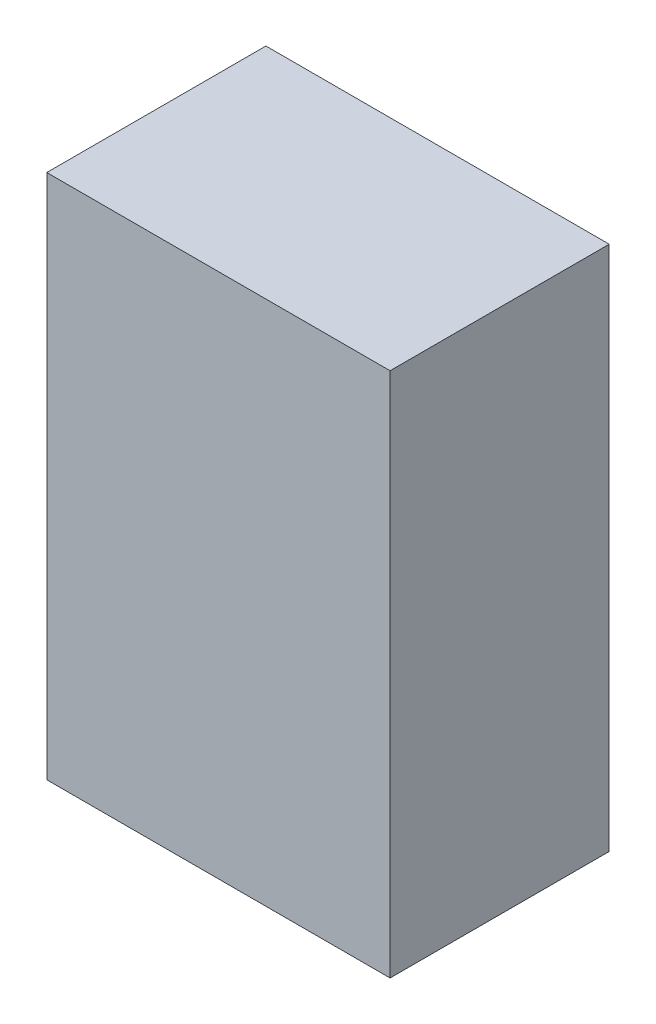
SolidWorks part; units mm, degrees
ref_plane "Front Plane" through (0, 0, 0) normal (0, 0, 1) x (1, 0, 0)
ref_plane "Top Plane" through (0, 0, 0) normal (0, 1, 0) x (1, 0, 0)
ref_plane "Right Plane" through (0, 0, 0) normal (1, 0, 0) x (0, 0, -1)
sketch "Sketch2" plane through (0, 0, 0) normal (0, 1, 0) x (1, 0, 0)
  line L1 (0, 0) -> (35.25, 0)
  line L2 (0, 0) -> (0, 22.5)
  line L3 (0, 22.5) -> (35.25, 22.5)
  line L4 (35.25, 0) -> (35.25, 22.5)
  dimension "D1" = 35.25
  dimension "D2" = 22.5
extrude "Boss-Extrude1" add sketch "Sketch2" along normal blind 54
